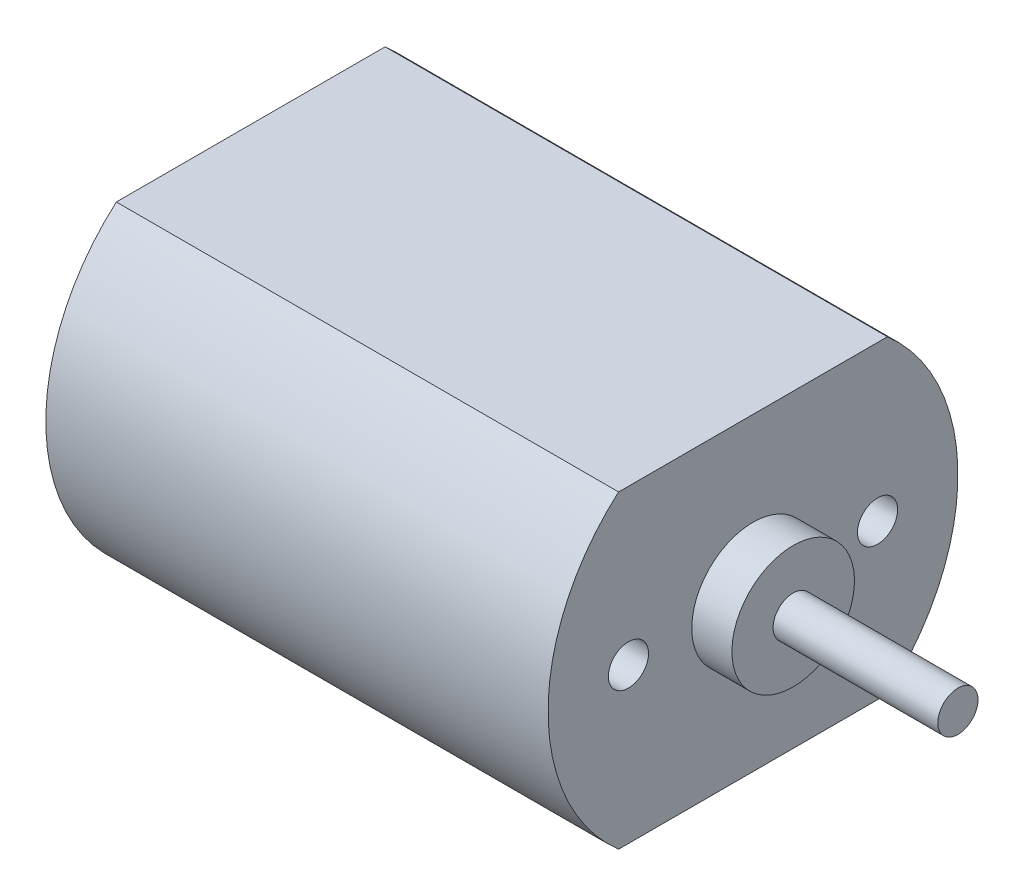
SolidWorks part; units mm, degrees
material "普通碳钢"
ref_plane "前视基准面" through (0, 0, 0) normal (0, 0, 1) x (1, 0, 0)
ref_plane "上视基准面" through (0, 0, 0) normal (0, 1, 0) x (1, 0, 0)
ref_plane "右视基准面" through (0, 0, 0) normal (1, 0, 0) x (0, 0, -1)
sketch "草图1" plane through (0, 0, 0) normal (0, 0, 1) x (1, 0, 0)
  line L0 (25, 7.15) -> (25, 0)
  line L3 (0, 0) -> (25, 0)
  line L7 (25, 7.15) -> (27, 7.15)
  line L11 (27, 9.2) -> (35.2, 9.2)
  line L12 (35.2, 10.2) -> (35.2, 9.2)
  line L13 (27, 9.2) -> (27, 7.15)
  line L14 (0, 7.15) -> (0, 0)
  line L17 (0, 7.15) -> (-1.6, 7.15)
  line L18 (-1.6, 10.2) -> (-1.6, 7.15)
  line L20 (-1.6, 10.2) -> (35.2, 10.2)
  dimension "D1" = 25
  dimension "D2" = 1
  dimension "D3" = 36.8
  dimension "D4" = 2
  dimension "D5" = 8.2
  dimension "D6" = 3.05
  dimension "D7" = 7.15
  dimension "D8" = 2.05
  dimension "D9" = 90
  dimension "D10" = 90
  dimension "D11" = 7.15
revolve "旋转3" add sketch "草图1" angle 360 about L20
sketch "草图2" plane through (25, 0, 0) normal (1, 0, 0) x (0, 0, -1)
  line L0 (-10.2, 10.2) -> (10.2, 10.2) construction
  line L1 (-6.6895, 17.9) -> (6.6895, 17.9)
  line L2 (-6.6895, 2.5) -> (6.6895, 2.5)
  circle A0 centre (0, 10.2) radius 10.2 construction
  arc A1 (-6.6895, 2.5) -> (6.6895, 2.5) centre (0, 10.2) ccw
  arc A2 (6.6895, 17.9) -> (-6.6895, 17.9) centre (0, 10.2) ccw
  dimension "D1" = 7.7
extrude "切除-拉伸1" cut sketch "草图2" against normal blind 36
sketch "草图3" plane through (25, 0, 0) normal (1, 0, 0) x (0, 0, -1)
  line L0 (0, 17.9) -> (0, 2.5) construction
  line L1 (-6.6895, 17.9) -> (6.6895, 17.9) construction
  line L2 (6.6895, 2.5) -> (-6.6895, 2.5) construction
  line L3 (-10.2, 10.2) -> (10.2, 10.2) construction
  circle A0 centre (-6.2, 10.2) radius 1
  arc A1 (-6.6895, 17.9) -> (-6.6895, 2.5) centre (0, 10.2) ccw construction
  arc A2 (6.6895, 2.5) -> (6.6895, 17.9) centre (0, 10.2) ccw construction
  circle A3 centre (6.2, 10.2) radius 1
  point P17 (0, 10.2)
  dimension "D2" = 2
  dimension "D1" = 6.2
extrude "切除-拉伸2" cut sketch "草图3" against normal blind 8
sketch "草图4" plane through (0, 0, 0) normal (-1, 0, 0) x (0, 0, 1)
  line L4 (6.5, 3) -> (-6.5, 3)
  line L5 (-6.5, 17.4) -> (6.5, 17.4)
  arc A4 (-6.5, 17.4) -> (-6.5, 3) centre (0, 10.2) ccw
  arc A5 (6.5, 3) -> (6.5, 17.4) centre (0, 10.2) ccw
extrude "切除-拉伸4" cut sketch "草图4" against normal blind 0.6
